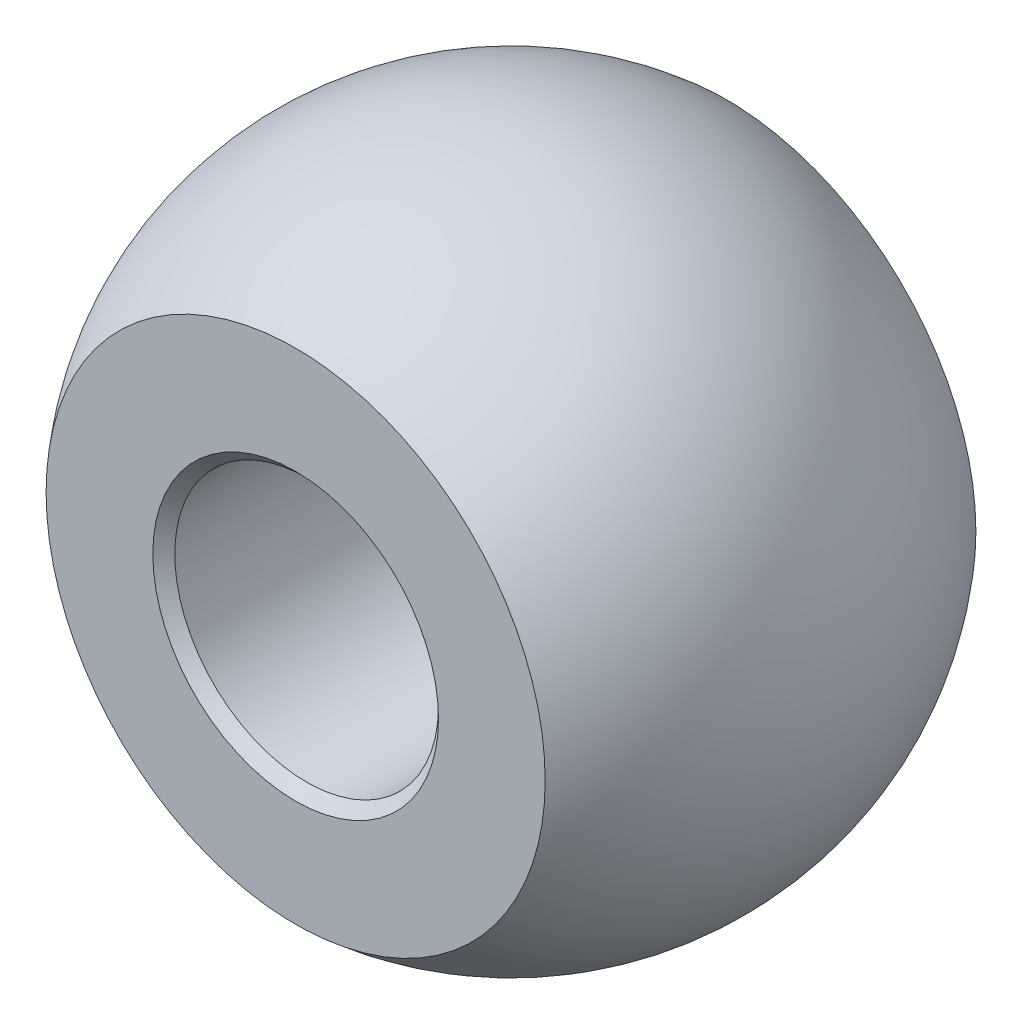
SolidWorks part; units mm, degrees
ref_plane "Top Plane" through (0, 0, 0) normal (0, 0, 1) x (1, 0, 0)
ref_plane "Front Plane" through (0, 0, 0) normal (0, 1, 0) x (1, 0, 0)
ref_plane "Right Plane" through (0, 0, 0) normal (1, 0, 0) x (0, 0, -1)
sketch "Sketch1" plane through (0, 0, 0) normal (0, 0, 1) x (1, 0, 0)
  line L1 (0, 3.75) -> (0, -3.75)
  arc A1 (0, -3.75) -> (0, 3.75) centre (0, 0) ccw
  dimension "D1" = 7.5
revolve "Revolve1" add sketch "Sketch1" angle 360 about L1
sketch "Sketch2" plane through (0, 0, 0) normal (1, 0, 0) x (0, 0, -1)
  line L0 (0, 0) -> (0, 1.219) construction
  line L1 (-4.45, 3.8) -> (-2.45, 3.8)
  line L2 (-4.45, 3.8) -> (-4.45, -3.8)
  line L3 (-4.45, -3.8) -> (-2.45, -3.8)
  line L4 (-2.45, 3.8) -> (-2.45, -3.8)
  line L5 (0.0734, 0) -> (5.1223, 0) construction
  line L6 (4.45, -3.8) -> (2.45, -3.8)
  line L7 (2.45, 3.8) -> (2.45, -3.8)
  line L8 (4.45, 3.8) -> (2.45, 3.8)
  line L9 (4.45, 3.8) -> (4.45, -3.8)
  point P7 (0, 0)
  point P8 (-2.45, 0)
  dimension "D1" = 2.45
  dimension "D2" = 2
  dimension "D3" = 7.6
extrude "Cut-Extrude1" cut sketch "Sketch2" against normal through all both and the other way through all
sketch "Sketch3" plane through (0, 0, 2.45) normal (0, 0, 1) x (1, 0, 0)
  circle A0 centre (0, 0) radius 1.5
  point P2 (0, 0)
  dimension "D1" = 3
extrude "Cut-Extrude2" cut sketch "Sketch3" against normal through all both
chamfer "Chamfer1" distance 0.125 angle 45 2 edges at (1.5, 0, 2.45) (1.5, 0, -2.45)
